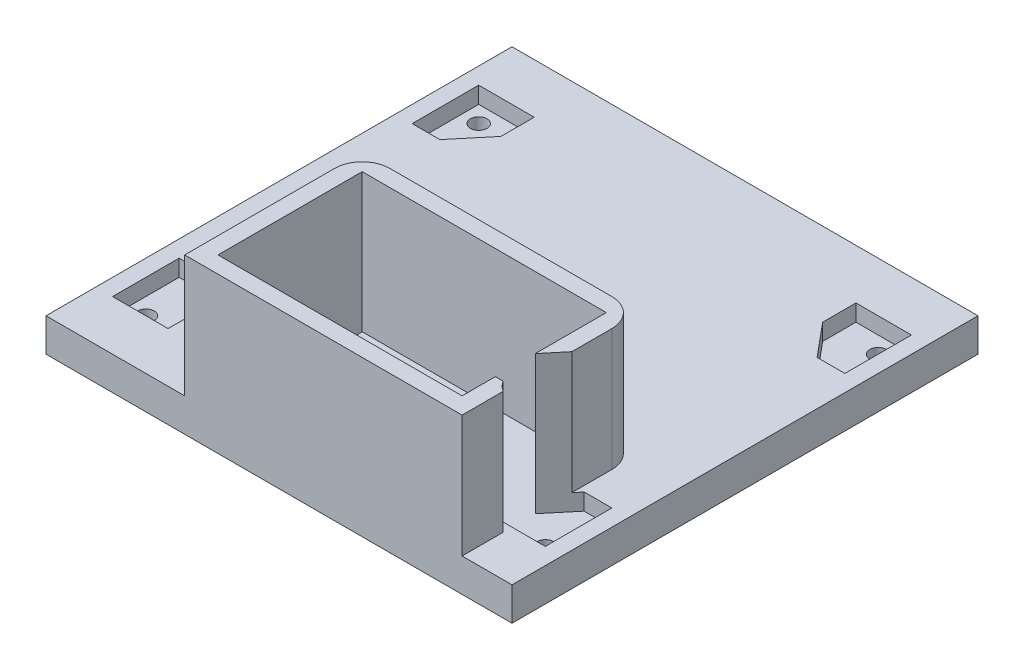
SolidWorks part; units mm, degrees
other "Markup1"
sketch "Sketch7"
sketch "Sketch12" plane through (84, 28, 0) normal (0.1424, 0.9893, 0.0306) x (0.9898, -0.1423, -0.003)
sketch "Sketch14" plane through (84, 28, 0) normal (0.1424, 0.9893, 0.0306) x (0.9898, -0.1423, -0.003)
sketch "Sketch15" plane through (84, 28, 0) normal (0.1424, 0.9893, 0.0306) x (0.9898, -0.1423, -0.003)
sketch "Sketch16" plane through (84, 28, 0) normal (0.1424, 0.9893, 0.0306) x (0.9898, -0.1423, -0.003)
material "PVB"
ref_plane "Front Plane" through (0, 0, 0) normal (0, 0, 1) x (1, 0, 0)
ref_plane "Top Plane" through (0, 0, 0) normal (0, 1, 0) x (1, 0, 0)
ref_plane "Right Plane" through (0, 0, 0) normal (1, 0, 0) x (0, 0, -1)
sketch "Sketch1" plane through (0, 0, 0) normal (0, 1, 0) x (1, 0, 0)
  line L1 (0, 0) -> (84, 0)
  line L2 (0, 0) -> (0, 84)
  line L3 (0, 84) -> (84, 84)
  line L4 (84, 0) -> (84, 84)
  dimension "D1" = 84
  dimension "D2" = 84
extrude "Boss-Extrude1" add sketch "Sketch1" along normal blind 6
sketch "Sketch2" plane through (0, 6, 0) normal (0, 1, 0) x (1, 0, 0)
  line L0 (84, 84) -> (0, 84) construction
  line L1 (0, 84) -> (0, 0) construction
  line L2 (0, 0) -> (84, 0) construction
  line L3 (84, 0) -> (84, 84) construction
  circle A0 centre (6, 72) radius 1.5
  circle A1 centre (6, 12) radius 1.5
  circle A2 centre (78, 12) radius 1.5
  circle A3 centre (78, 72) radius 1.5
  dimension "D1" = 3
  dimension "D2" = 3
  dimension "D3" = 3
  dimension "D4" = 3
  dimension "D6" = 6
  dimension "D7" = 12
  dimension "D8" = 6
  dimension "D9" = 6
  dimension "D10" = 12
  dimension "D11" = 6
  dimension "D5" = 12
  dimension "D12" = 12
extrude "Cut-Extrude1" cut sketch "Sketch2" against normal through all
ref_plane "Plane1" through (0, 0, -42) normal (0, 0, 1) x (1, 0, 0)
sketch "Sketch4" plane through (0, 6, 0) normal (0, 1, 0) x (1, 0, 0)
  line L0 (3, 21) -> (3, 9)
  line L1 (3, 9) -> (13, 9)
  line L2 (13, 15) -> (8, 21)
  line L3 (3, 21) -> (8, 21)
  line L4 (8, 21) -> (13, 15)
  line L5 (13, 15) -> (13, 9)
  line L6 (0, 84) -> (0, 0) construction
  line L7 (0, 0) -> (84, 0) construction
  circle A0 centre (6, 12) radius 1.5
  circle A1 centre (6, 12) radius 1.5 construction
  circle M21 centre (6, 12) radius 1.5
  dimension "D1" = 3
  dimension "D2" = 9
  dimension "D3" = 12
  dimension "D4" = 10
  dimension "D5" = 6
  dimension "D6" = 5
extrude "Cut-Extrude4" cut sketch "Sketch4" against normal blind 3 contours L5 L2 L3 L0 L1 M21
mirror "Mirror2" about plane through (0, 0, -42) normal (0, 0, 1) of "Cut-Extrude4"
ref_plane "Plane2" through (42, 0, 0) normal (-1, 0, 0) x (0, 0, 1)
mirror "Mirror3" about plane through (42, 0, 0) normal (-1, 0, 0) of "Mirror2", "Cut-Extrude4"
sketch "Sketch5" plane through (0, 6, 0) normal (0, 1, 0) x (1, 0, 0)
  line L0 (25, 32) -> (25, 0)
  line L1 (25, 32) -> (75, 32)
  line L2 (25, 0) -> (75, 0)
  line L3 (75, 32) -> (75, 0)
  line L4 (25, 32) -> (75, 0) construction
  line L5 (25, 0) -> (75, 32) construction
  line L7 (42, 3.3) -> (42, -3.3) construction
  line L12 (0, 0) -> (84, 0) construction
  point P1 (50, 16)
  dimension "D1" = 50
  dimension "D2" = 32
  dimension "D3" = 8
extrude "Boss-Extrude2" add sketch "Sketch5" along normal blind 22
sketch "Sketch6" plane through (0, 28, 0) normal (0, 1, 0) x (1, 0, 0)
  line L14 (72, 29) -> (28, 29)
  line L15 (28, 29) -> (28, 3)
  line L16 (28, 3) -> (72, 3)
  line L17 (72, 3) -> (72, 29)
  line L18 (72, 29) -> (28, 29)
  line L19 (28, 29) -> (28, 3)
  line L20 (28, 3) -> (72, 3)
  line L21 (72, 3) -> (72, 29)
  dimension "D1" = 3
extrude "Cut-Extrude5" cut sketch "Sketch6" against normal blind 25
sketch "Sketch8" plane through (0, 28, 0) normal (0, 1, 0) x (1, 0, 0)
  line L0 (81, 21) -> (81, 9) construction
  line L1 (81, 9) -> (72, 9) construction
  line L2 (72, 16.2) -> (76, 21) construction
  line L3 (81, 21) -> (76, 21) construction
  line L4 (75, 32) -> (25, 32)
  line L5 (25, 32) -> (25, 0)
  line L6 (25, 0) -> (75, 0)
  line L7 (75, 0) -> (75, 32)
  line L8 (75, 32) -> (25, 32)
  line L9 (25, 32) -> (25, 0)
  line L10 (25, 0) -> (75, 0)
  line L11 (75, 0) -> (75, 32)
  line L12 (81, 21) -> (81, 9)
  line L13 (81, 9) -> (72, 9)
  line L14 (72, 16.2) -> (76, 21)
  line L15 (81, 21) -> (76, 21)
  line L16 (72, 16.2) -> (72, 9)
  circle A0 centre (78, 12) radius 1.5 construction
  circle A1 centre (78, 12) radius 1.5
  circle A2 centre (78, 12) radius 5.5
  line M17 (72, 29) -> (72, 3)
  dimension "D2" = 11
  dimension "D1" = 0
extrude "Cut-Extrude14" cut sketch "Sketch8" against normal up to surface (22 mm away) contours L11 A2 L13 M17 | L13 A2 L11
sketch "Sketch13" plane through (0, 3, 0) normal (0, 1, 0) x (1, 0, 0)
  line L5 (28, 29) -> (28, 3)
  line L6 (72, 9) -> (81, 9)
  line L7 (81, 9) -> (81, 21)
  line L8 (81, 21) -> (76, 21)
  line L9 (76, 21) -> (72, 16.2)
  line L11 (72, 9) -> (81, 9)
  line L12 (81, 9) -> (81, 21)
  line L13 (81, 21) -> (76, 21)
  line L14 (76, 21) -> (72, 16.2)
  line L19 (28, 29) -> (28, 3)
  line L20 (72, 29) -> (28, 29)
  line L22 (72, 3) -> (72, 9)
  line L23 (72, 3) -> (72, 9)
  line L24 (72, 16.2) -> (72, 29)
  line L25 (72, 16.2) -> (72, 29)
  line L26 (72, 29) -> (28, 29)
  line L28 (28, 3) -> (72, 3)
  line L29 (28, 3) -> (72, 3)
  dimension "D1" = 0
extrude "Cut-Extrude15" cut sketch "Sketch13" along normal through all
fillet "Fillet2" radius 5 2 edges at (25, 17, -32) (75, 17, -32)
